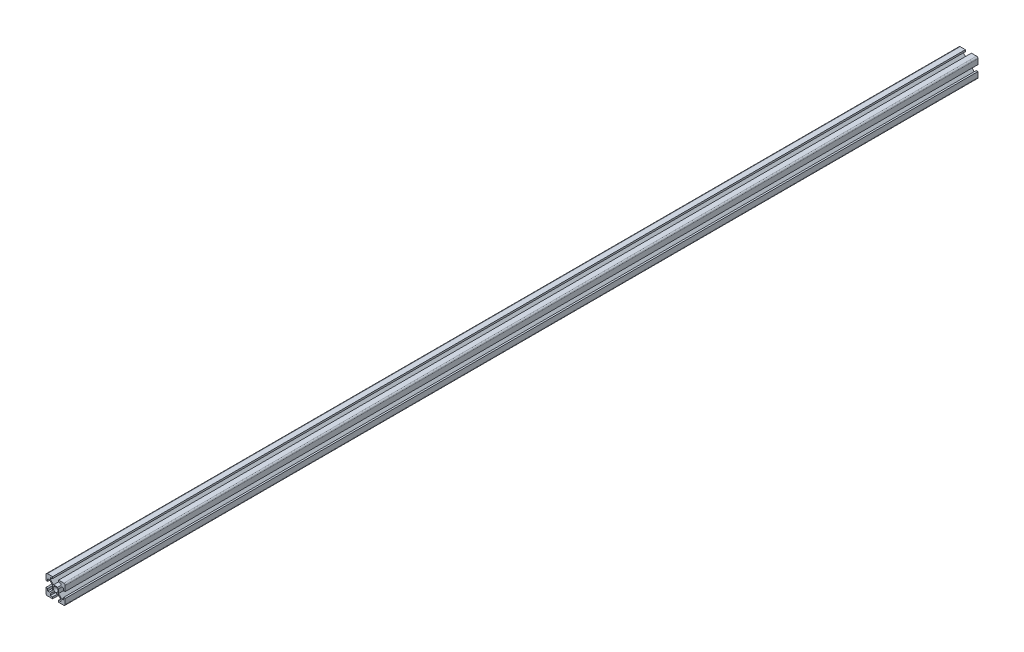
SolidWorks part; units mm, degrees
ref_plane "前视基准面" through (0, 0, 0) normal (0, 0, 1) x (1, 0, 0)
ref_plane "上视基准面" through (0, 0, 0) normal (0, 1, 0) x (1, 0, 0)
ref_plane "右视基准面" through (0, 0, 0) normal (1, 0, 0) x (0, 0, -1)
sketch "草图1" plane through (0, 0, 0) normal (0, 0, 1) x (1, 0, 0)
  line L0 (-10, -3.1) -> (-8.2, -3.1)
  line L1 (-8.5, 10) -> (8.5, 10)
  line L2 (-10, 8.5) -> (-10, -8.5)
  line L3 (-8.5, -10) -> (8.5, -10)
  line L4 (10, 8.5) -> (10, -8.5)
  line L5 (-10, 10) -> (10, -10) construction
  line L6 (-10, -10) -> (10, 10) construction
  line L7 (-3.0541, 3.1) -> (3.0541, 3.1)
  line L8 (-3.0541, 3.1) -> (-3.0541, -3.1)
  line L9 (-3.0541, -3.1) -> (3.0541, -3.1)
  line L10 (3.0541, 3.1) -> (3.0541, -3.1)
  line L11 (-3.0541, 3.1) -> (3.0541, -3.1) construction
  line L12 (-3.0541, -3.1) -> (3.0541, 3.1) construction
  line L13 (-8.2, -3.1) -> (-8.2, -5.5)
  line L14 (-8.2, -5.5) -> (-6.3971, -5.5)
  line L15 (-6.3971, -5.5) -> (-3.0541, -2.1571)
  line L16 (-5.5, 6.3971) -> (-2.1571, 3.0541)
  line L17 (-5.5, 8.2) -> (-5.5, 6.3971)
  line L18 (-3.1, 8.2) -> (-5.5, 8.2)
  line L19 (-3.1, 10) -> (-3.1, 8.2)
  line L20 (6.3971, 5.5) -> (3.0541, 2.1571)
  line L21 (8.2, 5.5) -> (6.3971, 5.5)
  line L22 (8.2, 3.1) -> (8.2, 5.5)
  line L23 (10, 3.1) -> (8.2, 3.1)
  line L24 (5.5, -6.3971) -> (2.1571, -3.0541)
  line L25 (5.5, -8.2) -> (5.5, -6.3971)
  line L26 (3.1, -8.2) -> (5.5, -8.2)
  line L27 (3.1, -10) -> (3.1, -8.2)
  line L28 (-3.1, -10) -> (-3.1, -8.2)
  line L29 (-3.1, -8.2) -> (-5.5, -8.2)
  line L30 (-5.5, -8.2) -> (-5.5, -6.3971)
  line L31 (-5.5, -6.3971) -> (-2.1571, -3.0541)
  line L32 (-8.2, 5.5) -> (-6.3971, 5.5)
  line L33 (-6.3971, 5.5) -> (-3.0541, 2.1571)
  line L34 (-8.2, 3.1) -> (-8.2, 5.5)
  line L35 (-10, 3.1) -> (-8.2, 3.1)
  line L36 (5.5, 8.2) -> (5.5, 6.3971)
  line L37 (5.5, 6.3971) -> (2.1571, 3.0541)
  line L38 (3.1, 8.2) -> (5.5, 8.2)
  line L39 (3.1, 10) -> (3.1, 8.2)
  line L40 (8.2, -5.5) -> (6.3971, -5.5)
  line L41 (6.3971, -5.5) -> (3.0541, -2.1571)
  line L42 (8.2, -3.1) -> (8.2, -5.5)
  line L43 (10, -3.1) -> (8.2, -3.1)
  circle A0 centre (0, 0) radius 2.5
  arc A1 (-10, 8.5) -> (-8.5, 10) centre (-8.5, 8.5) cw
  arc A2 (-10, -8.5) -> (-8.5, -10) centre (-8.5, -8.5) ccw
  arc A3 (8.5, 10) -> (10, 8.5) centre (8.5, 8.5) cw
  arc A4 (10, -8.5) -> (8.5, -10) centre (8.5, -8.5) cw
  point P0 (0, 0)
  point P20 (0, 0)
  point P26 (0, 0)
  point P32 (0, 0)
  point P38 (0, 0)
  point P60 (0, 0)
  dimension "D1" = 4
  dimension "D3" = 1.5
  dimension "D4" = 1.5
  dimension "D5" = 1.5
  dimension "D2" = 4
extrude "凸台-拉伸1" add sketch "草图1" along normal blind 950
